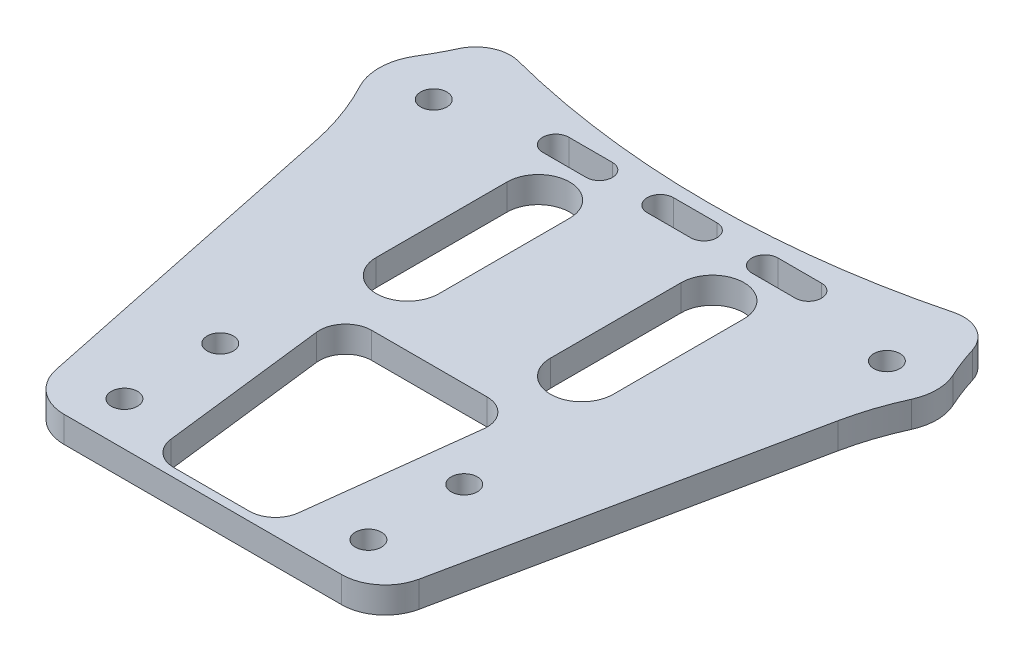
SolidWorks part; units mm, degrees
material "Thornel Mat VMA"
ref_plane "前视基准面" through (0, 0, 0) normal (0, 0, 1) x (1, 0, 0)
ref_plane "上视基准面" through (0, 0, 0) normal (0, 1, 0) x (1, 0, 0)
ref_plane "右视基准面" through (0, 0, 0) normal (1, 0, 0) x (0, 0, -1)
sketch "草图1" plane through (0, 0, 0) normal (0, 1, 0) x (1, 0, 0)
  line L0 (-17.5, -25) -> (-30, -25)
  line L1 (30, -25) -> (17.5, -25)
  line L2 (30, -25) -> (30, 25)
  line L4 (-30, -25) -> (-30, 25)
  line L5 (30, -25) -> (-30, 25) construction
  line L6 (30, 25) -> (-30, -25) construction
  line L7 (17.5, -45) -> (-17.5, -45)
  line L8 (17.5, -45) -> (17.5, -25)
  line L10 (-17.5, -45) -> (-17.5, -25)
  line L11 (17.5, -45) -> (-17.5, -25) construction
  line L12 (17.5, -25) -> (-17.5, -45) construction
  line L13 (0, 52.7731) -> (0, -69.0929) construction
  line L14 (30, 25) -> (30, 29.6061)
  line L15 (-30, 25) -> (-30, 29.6061)
  line L16 (-2.5, 22) -> (2.5, 22) construction
  line L17 (9.5, 20.5) -> (14.5, 20.5)
  line L18 (-2.5, 23.5) -> (2.5, 23.5)
  line L19 (-2.5, 20.5) -> (2.5, 20.5)
  line L20 (9.5, 23.5) -> (14.5, 23.5)
  line L21 (9.5, 22) -> (14.5, 22) construction
  line L25 (-14.5, 22) -> (-9.5, 22) construction
  line L26 (-14.5, 23.5) -> (-9.5, 23.5)
  line L27 (-14.5, 20.5) -> (-9.5, 20.5)
  line L31 (21.5, 23.5) -> (26.5, 23.5) [skipped]
  line L32 (21.5, 20.5) -> (26.5, 20.5) [skipped]
  line L35 (-26.5, 22) -> (-21.5, 22) construction
  line L36 (-26.5, 23.5) -> (-21.5, 23.5) [skipped]
  line L37 (-26.5, 20.5) -> (-21.5, 20.5) [skipped]
  line L38 (-26.5, 22) -> (-21.5, 22) construction
  line L39 (-26.5, 23.5) -> (-21.5, 23.5) [skipped]
  line L40 (-26.5, 20.5) -> (-21.5, 20.5) [skipped]
  circle A0 centre (-14, -17) radius 1.5
  circle A1 centre (14, -17) radius 1.5
  arc A2 (-30, 29.6061) -> (30, 29.6061) centre (0, 125) ccw
  circle A3 centre (-14, -28) radius 1.5
  circle A5 centre (14, -28) radius 1.5
  arc A7 (-30, 25.4209) -> (30, 25.4209) centre (0, 125) ccw construction
  arc A9 (-2.5, 23.5) -> (-2.5, 20.5) centre (-2.5, 22) ccw
  arc A10 (2.5, 20.5) -> (2.5, 23.5) centre (2.5, 22) ccw
  arc A11 (9.5, 23.5) -> (9.5, 20.5) centre (9.5, 22) ccw
  arc A12 (14.5, 20.5) -> (14.5, 23.5) centre (14.5, 22) ccw
  arc A15 (-14.5, 23.5) -> (-14.5, 20.5) centre (-14.5, 22) ccw
  arc A16 (-9.5, 20.5) -> (-9.5, 23.5) centre (-9.5, 22) ccw
  arc A19 (21.5, 23.5) -> (21.5, 20.5) centre (21.5, 22) ccw [skipped]
  arc A20 (26.5, 20.5) -> (26.5, 23.5) centre (26.5, 22) ccw [skipped]
  arc A25 (-26.5, 23.5) -> (-26.5, 20.5) centre (-26.5, 22) ccw [skipped]
  arc A26 (-21.5, 20.5) -> (-21.5, 23.5) centre (-21.5, 22) ccw [skipped]
  point P0 (0, 0)
  point P5 (0, -35)
  point P31 (0, 22)
  point P36 (-24, 22)
  point P38 (12, 22)
  point P52 (-12, 22)
  point P76 (-24, 22)
  point P83 (-24, 22)
  dimension "D5" = 3
  dimension "D7" = 14
  dimension "D8" = 125
  dimension "D9" = 3
  dimension "D10" = 17
  dimension "D11" = 11
  dimension "D12" = 12
  dimension "D13" = 208
  dimension "D14" = 1.5
  dimension "D1" = 50
  dimension "D2" = 60
  dimension "D3" = 20
  dimension "D4" = 35
  dimension "D6" = 30
  dimension "D15" = 5
  dimension "D16" = 22
  dimension "D19" = 12
  dimension "D17" = 3
  dimension "D18" = 3
extrude "凸台-拉伸1" add sketch "草图1" along normal blind 3
sketch "草图2" plane through (0, 3, 0) normal (0, 1, 0) x (1, 0, 0)
  line L0 (-10, 15.5) -> (-10, 0.5) construction
  line L1 (0, 59.8002) -> (0, -61.1392) construction
  line L2 (-6.4, 15.5) -> (-6.4, 0.5)
  line L3 (-13.6, 15.5) -> (-13.6, 0.5)
  line L4 (10, 15.5) -> (10, 0.5) construction
  line L5 (6.4, 15.5) -> (6.4, 0.5)
  line L6 (13.6, 15.5) -> (13.6, 0.5)
  arc A0 (-6.4, 15.5) -> (-13.6, 15.5) centre (-10, 15.5) ccw
  arc A1 (-13.6, 0.5) -> (-6.4, 0.5) centre (-10, 0.5) ccw
  arc A2 (6.4, 15.5) -> (13.6, 15.5) centre (10, 15.5) cw
  arc A3 (13.6, 0.5) -> (6.4, 0.5) centre (10, 0.5) cw
  circle A4 centre (-26, 19.5) radius 1.5
  circle A5 centre (26, 19.5) radius 1.5
  point P4 (-10, 8)
  point P12 (10, 8)
  dimension "D4" = 3
  dimension "D5" = 16
  dimension "D1" = 3.6
  dimension "D2" = 15
  dimension "D3" = 10
  dimension "D6" = 19
  dimension "D7" = 8
extrude "切除-拉伸1" cut sketch "草图2" against normal through all
sketch "草图3" plane through (0, 3, 0) normal (0, 1, 0) x (1, 0, 0)
  line L0 (-30, -25) -> (-17.5, -45)
  line L1 (-17.5, -45) -> (-17.5, -25)
  line L2 (-17.5, -25) -> (-30, -25)
  line L3 (17.5, -25) -> (17.5, -45)
  line L4 (17.5, -45) -> (30, -25)
  line L5 (30, -25) -> (17.5, -25)
extrude "凸台-拉伸2" add sketch "草图3" against normal blind 3
sketch "草图4" plane through (0, 3, 0) normal (0, 1, 0) x (1, 0, 0)
  line L0 (-30, 15) -> (-17.5, -45)
  line L1 (-30, 29.6061) -> (-30, -25) construction
  line L2 (-17.5, -45) -> (-30, -25)
  line L3 (-30, -25) -> (-30, 15)
  line L4 (0, 42.1413) -> (0, -70.3529) construction
  line L5 (17.5, -45) -> (30, -25)
  line L6 (30, 15) -> (17.5, -45)
  line L7 (30, -25) -> (30, 15)
  dimension "D1" = 40
extrude "切除-拉伸2" cut sketch "草图4" against normal through all
sketch "草图6" plane through (0, 3, 0) normal (0, 1, 0) x (1, 0, 0)
  line L0 (0, 34.3534) -> (0, -64.4461) construction
  line L1 (-10, -7) -> (10, -7)
  line L2 (-7, -32) -> (7, -32)
  line L3 (-10, -7) -> (-7, -32)
  line L4 (10, -7) -> (7, -32)
  line L5 (-17.5, -45) -> (17.5, -45) construction
  point P7 (0, -7)
  point P10 (0, -32)
  dimension "D1" = 13
  dimension "D2" = 20
  dimension "D3" = 14
  dimension "D4" = 25
extrude "切除-拉伸3" cut sketch "草图6" against normal blind 3
fillet "圆角1" radius 3 4 edges at (7, 1.5, 32) (-7, 1.5, 32) (-10, 1.5, 7) (10, 1.5, 7)
sketch "草图8" plane through (0, 3, 0) normal (0, 1, 0) x (1, 0, 0)
  line L0 (-17.5, -45) -> (-17.0833, -47)
  line L1 (-17.5, -45) -> (-30, 15) construction
  line L2 (17.5, -45) -> (17.0833, -47)
  line L3 (30, 15) -> (17.5, -45) construction
  line L4 (-17.0833, -47) -> (17.0833, -47)
  line L5 (-17.5, -45) -> (17.5, -45)
  dimension "D1" = 2
extrude "凸台-拉伸3" add sketch "草图8" against normal blind 3
fillet "圆角3" radius 4 6 edges at (30, 1.5, -15) (30, 1.5, -29.6061) (-30, 1.5, -29.6061) (-30, 1.5, -15) (17.0833, 1.5, 47) (-17.0833, 1.5, 47)
sketch "草图9" plane through (0, 3, 0) normal (0, 1, 0) x (1, 0, 0)
  line L1 (20, -61) -> (-20, -61)
  line L2 (20, -61) -> (20, -33)
  line L3 (20, -33) -> (-20, -33)
  line L4 (-20, -61) -> (-20, -33)
  line L5 (20, -61) -> (-20, -33) construction
  line L6 (20, -33) -> (-20, -61) construction
  line L8 (-13.8308, -47) -> (13.8308, -47) construction
  line L9 (-17.7467, -43.8158) -> (-29.9159, 14.5964) construction
  point P0 (0, -47)
  dimension "D1" = 28
  dimension "D2" = 40
extrude "切除-拉伸4" cut sketch "草图9" against normal blind 10
fillet "圆角4" radius 5 2 edges at (20, 1.5, 33) (-20, 1.5, 33)
sketch "草图11" plane through (0, 3, 0) normal (0, 1, 0) x (1, 0, 0)
  circle A0 centre (-26, 19.5) radius 6.2753
  circle A1 centre (-26, 19.5) radius 1.5
  circle A2 centre (26, 19.5) radius 1.5
  circle A3 centre (26, 19.5) radius 5.7192
  dimension "D1" = 3
  dimension "D2" = 3
extrude "凸台-拉伸4" add sketch "草图11" against normal blind 3
fillet "圆角5" radius 30 4 edges at (30, 1.5, -15.4122) (30, 1.5, -23.5878) (-29.9159, 1.5, -14.5964) (-29.9999, 1.5, -24.3353)
